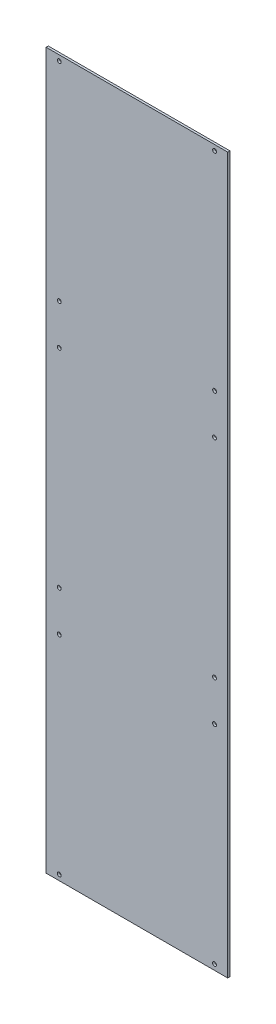
SolidWorks part; units mm, degrees
material "6061 Alloy"
ref_plane "Frontal" through (0, 0, 0) normal (0, 0, 1) x (1, 0, 0)
ref_plane "Superior" through (0, 0, 0) normal (0, 1, 0) x (1, 0, 0)
ref_plane "Direito" through (0, 0, 0) normal (1, 0, 0) x (0, 0, -1)
sketch "Sketch1" plane through (0, 0, 0) normal (0, 0, 1) x (1, 0, 0)
  line L1 (-41.5, -163.5) -> (41.5, -163.5)
  line L2 (-41.5, -163.5) -> (-41.5, 163.5)
  line L3 (-41.5, 163.5) -> (41.5, 163.5)
  line L4 (41.5, -163.5) -> (41.5, 163.5)
  line L5 (-41.5, -163.5) -> (41.5, 163.5) construction
  line L6 (-41.5, 163.5) -> (41.5, -163.5) construction
  point P0 (0, 0)
  dimension "D1" = 327
  dimension "D2" = 83
extrude "Boss-Extrude1" add sketch "Sketch1" along normal mid plane 1
hole_wizard "M1.6 Clearance Hole1" positions "Sketch3" profile "Sketch2" hole size "M1.6" standard "DIN" end condition through all
sketch "Sketch3" plane through (0, 0, 0.5) normal (0, 0, 1) x (1, 0, 0)
  line L0 (41.5, 163.5) -> (-41.5, 163.5) construction
  line L1 (-41.5, 163.5) -> (-41.5, -163.5) construction
  line L2 (41.5, -163.5) -> (41.5, 163.5) construction
  line L3 (-41.5, -163.5) -> (41.5, -163.5) construction
  point P0 (-35.5, 161)
  point P2 (35.5, 161)
  point P4 (-35.5, 66)
  point P6 (35.5, 66)
  point P8 (-35.5, 47.5)
  point P10 (35.5, 47.5)
  point P12 (-35.5, -47.5)
  point P14 (35.5, -47.5)
  point P16 (-35.5, -66)
  point P18 (35.5, -66)
  point P20 (-35.5, -161)
  point P22 (35.5, -161)
  dimension "D1" = 2.5
  dimension "D2" = 6
  dimension "D3" = 6
  dimension "D4" = 2.5
  dimension "D5" = 95
  dimension "D6" = 18.5
  dimension "D7" = 95
  dimension "D8" = 18.5
sketch "Sketch2" plane through (-35.5, 161, 0.5) normal (1, 0, 0) x (0, -1, 0)
  line L0 (0, 0) -> (0, 1)
  line L1 (0, 1) -> (0.9, 1)
  line L2 (0.9, 1) -> (0.9, 0)
  line L5 (0.9, 0) -> (0, 0)
  line L11 (0, -6.35) -> (0, 107.95) construction
  dimension "Thru Hole Dia." = 1.8
  dimension "Thru Hole Depth" = 1
